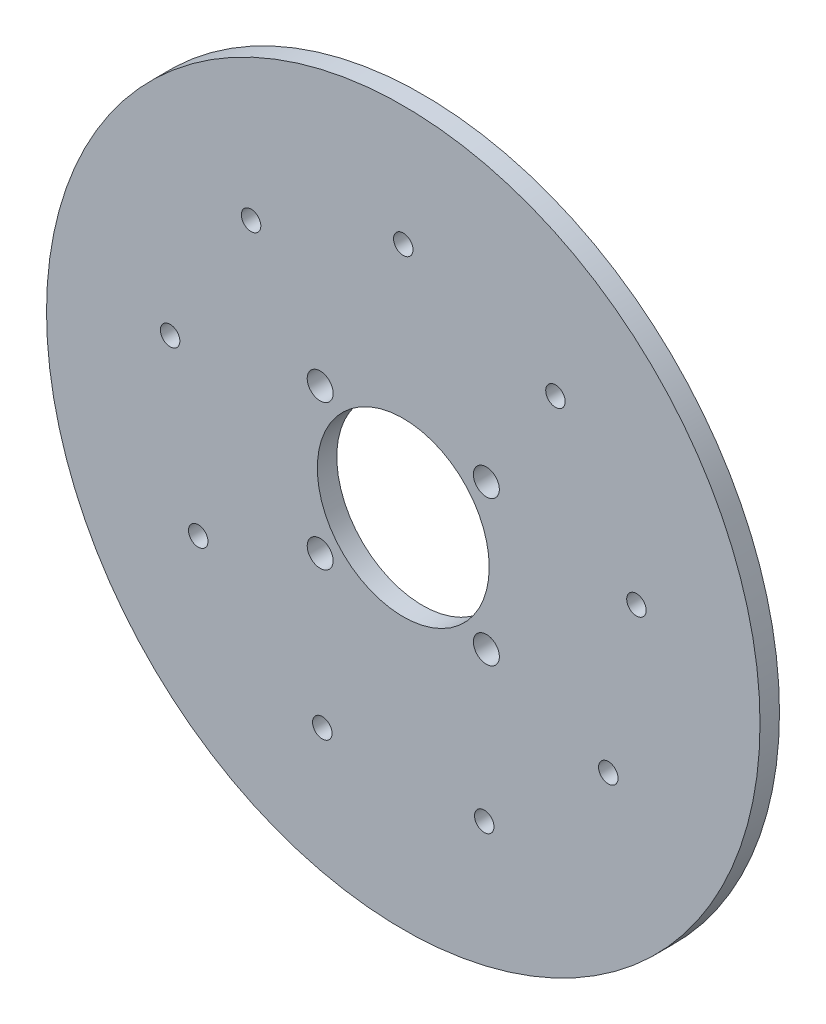
SolidWorks part; units mm, degrees
ref_plane "前视基准面" through (0, 0, 0) normal (0, 0, 1) x (1, 0, 0)
ref_plane "上视基准面" through (0, 0, 0) normal (0, 1, 0) x (1, 0, 0)
ref_plane "右视基准面" through (0, 0, 0) normal (1, 0, 0) x (0, 0, -1)
sketch "草图1" plane through (0, 0, 0) normal (0, 0, 1) x (1, 0, 0)
  line L0 (0, 35) -> (0, 36.5) construction
  circle A14 centre (0, 0) radius 55
  circle A15 centre (0, 36.5) radius 1.5
  circle A17 centre (23.4617, 27.9606) radius 1.5
  circle A18 centre (35.9455, 6.3382) radius 1.5
  circle A19 centre (31.6099, -18.25) radius 1.5
  circle A20 centre (12.4837, -34.2988) radius 1.5
  circle A21 centre (-12.4837, -34.2988) radius 1.5
  circle A22 centre (-31.6099, -18.25) radius 1.5
  circle A23 centre (-35.9455, 6.3382) radius 1.5
  circle A24 centre (-23.4617, 27.9606) radius 1.5
  circle A29 centre (0, 0) radius 13.25
  circle A30 centre (-12.8094, 11.1768) radius 2
  circle A31 centre (12.8094, 11.1768) radius 2
  circle A32 centre (12.8094, -11.1768) radius 2
  circle A33 centre (-12.8094, -11.1768) radius 2
  point P23 (0, 0)
  dimension "D1" = 110
  dimension "D2" = 36.5
  dimension "D3" = 9
  dimension "D4" = 4
  dimension "D5" = 17
  dimension "D6" = 3
  dimension "D8" = 26.5
extrude "凸台-拉伸1" add sketch "草图1" along normal blind 3
